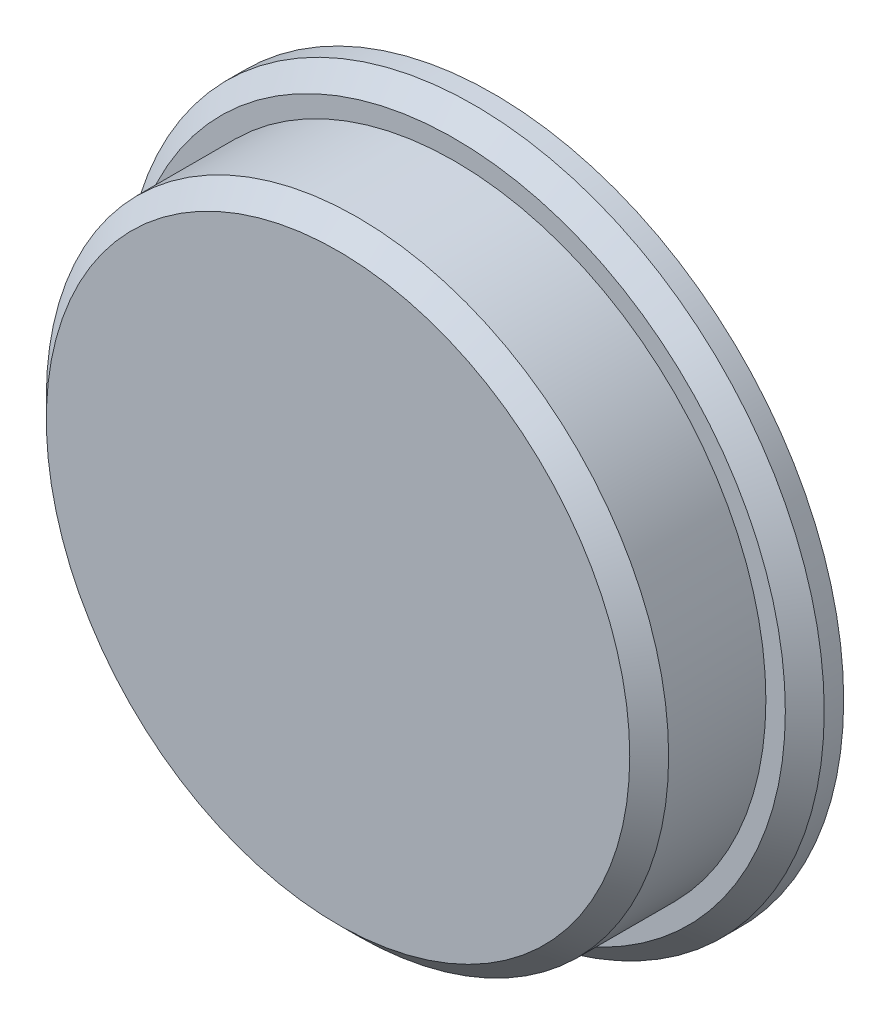
SolidWorks part; units mm, degrees
ref_plane "Plan de face" through (0, 0, 0) normal (0, 0, 1) x (1, 0, 0)
ref_plane "Plan de dessus" through (0, 0, 0) normal (0, 1, 0) x (1, 0, 0)
ref_plane "Plan de droite" through (0, 0, 0) normal (1, 0, 0) x (0, 0, -1)
sketch "Esquisse1" plane through (0, 0, 0) normal (0, 0, 1) x (1, 0, 0)
  circle A0 centre (0, 0) radius 9
  dimension "D1" = 18
extrude "Boss.-Extru.1" add sketch "Esquisse1" along normal blind 1
chamfer "Chanfrein1" distance 0.5 angle 45 1 edges at (9, 0, 1)
sketch "Esquisse2" plane through (0, 0, 1) normal (0, 0, 1) x (1, 0, 0)
  circle A0 centre (0, 0) radius 8
  dimension "D1" = 16
extrude "Boss.-Extru.2" add sketch "Esquisse2" along normal blind 3
chamfer "Chanfrein2" distance 0.5 angle 45 1 edges at (8, 0, 4)
